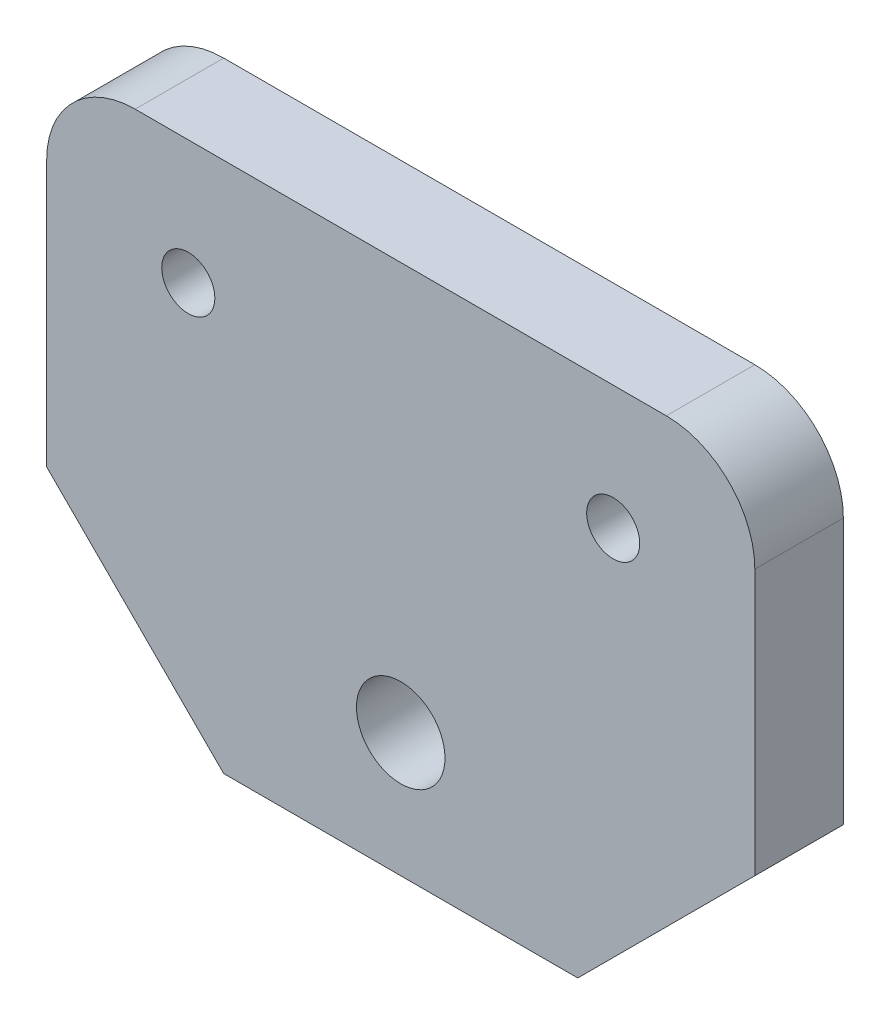
SolidWorks part; units mm, degrees
ref_plane "Plan de face" through (0, 0, 0) normal (0, 0, 1) x (1, 0, 0)
ref_plane "Plan de dessus" through (0, 0, 0) normal (0, 1, 0) x (1, 0, 0)
ref_plane "Plan de droite" through (0, 0, 0) normal (1, 0, 0) x (0, 0, -1)
sketch "Esquisse1" plane through (0, 0, 0) normal (0, 0, 1) x (1, 0, 0)
  line L1 (0, 0) -> (40, 0)
  line L2 (0, 0) -> (0, 30)
  line L3 (0, 30) -> (40, 30)
  line L4 (40, 0) -> (40, 30)
  dimension "D1" = 40
  dimension "D2" = 30
extrude "Boss.-Extru.1" add sketch "Esquisse1" along normal blind 5
sketch "Esquisse2" plane through (0, 0, 5) normal (0, 0, 1) x (1, 0, 0)
  line L0 (20, 0) -> (20, 30) construction
  line L1 (0, 0) -> (40, 0) construction
  line L2 (40, 30) -> (0, 30) construction
  circle A0 centre (8, 23) radius 1.5
  circle A1 centre (32, 23) radius 1.5
  circle A2 centre (20, 7) radius 2.5
  dimension "D1" = 5
  dimension "D2" = 3
  dimension "D3" = 23
  dimension "D4" = 7
  dimension "12" = 24
extrude "Enlèv. mat.-Extru.1" cut sketch "Esquisse2" against normal through all both and the other way through all
chamfer "Chanfrein1" distance 10 angle 45 2 edges at (40, 0, 2.5) (0, 0, 2.5)
fillet "Congé1" radius 5 2 edges at (40, 30, 2.5) (0, 30, 2.5)
